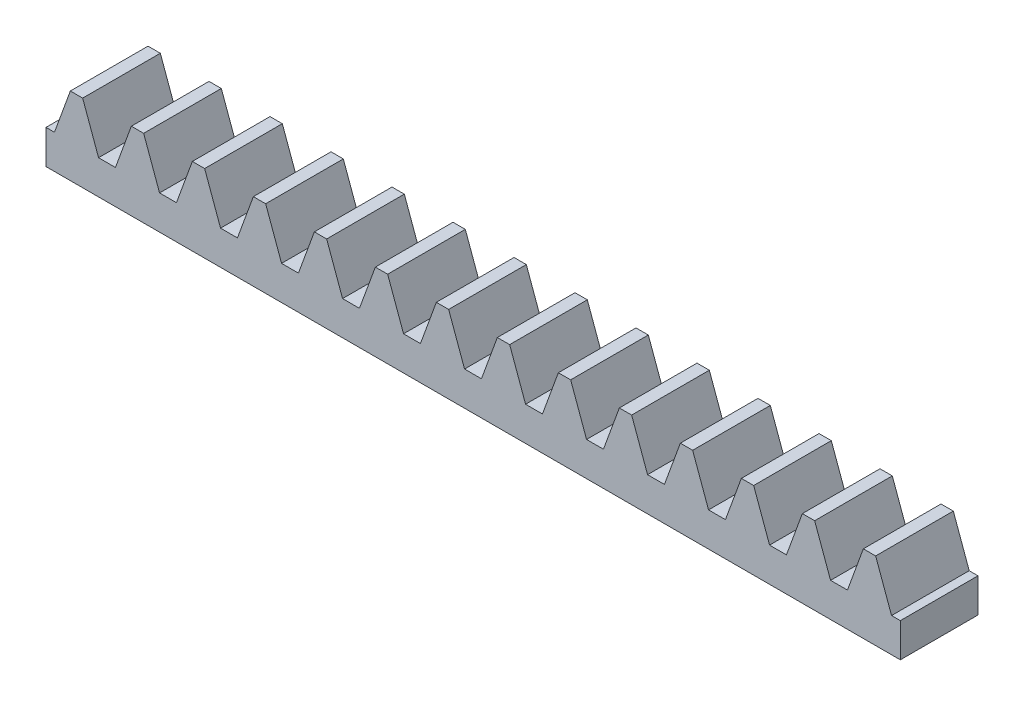
SolidWorks part; units mm, degrees
extrude "Blank" add sketch "BlankSke" against normal blind 10
sketch "BlankSke" plane through (0, 0, 0) normal (0, 0, 1) x (1, 0, 0)
  line L1 (0, 0) -> (110, 0)
  line L2 (0, 0) -> (0, 10)
  line L3 (0, 10) -> (110, 10)
  line L4 (110, 0) -> (110, 10)
  dimension "Length" = 110
  dimension "Blank_height" = 10
ref_plane "Plane1" through (0, 0, 0) normal (0, 0, 1) x (1, 0, 0)
ref_plane "Plane2" through (0, 0, 0) normal (0, 1, 0) x (1, 0, 0)
ref_plane "Plane3" through (0, 0, 0) normal (1, 0, 0) x (0, 0, -1)
sketch "HoldingSke" plane through (0, 0, 0) normal (0, 1, 0) x (1, 0, 0)
  line L0 (0, 0) -> (0.0557, 0.3961)
  line L1 (-15, 0) -> (100, 0) construction
  line L2 (0, 0) -> (-2.1039, 2.3779)
  line L3 (0, 0) -> (-11.863, 4.5341)
  line L4 (0, 0) -> (8.3015, 2.3804)
  line L5 (0, 0) -> (-23.7986, -8.8762)
  line L6 (0, 0) -> (-10.5278, -7.1032)
  line L9 (-71.009, 38.7566) -> (32.3572, 76.3788)
  line L10 (-76.2, 4.8779) -> (-68.7, 4.8779)
  line L11 (0, 0) -> (-10, 0)
  line L12 (-76.2, 101.6) -> (-76.113, 101.6)
  line L13 (24.9733, 27.94) -> (52.9518, 28.4284)
  line L14 (24.9733, 27.94) -> (24.9743, 27.94)
  line L15 (24.9733, 27.94) -> (100.4006, 29.5858)
  circle A0 centre (0, 0) radius 19.05
  circle A1 centre (0, 0) radius 3.75
  circle A2 centre (0, 0) radius 12.7
  dimension "MPH" = 7.5
  dimension "Diameter" = 38.1
  dimension "Num_teeth" = 16
  dimension "Pitch" = 0.4
  dimension "Show_teeth" = 998
  dimension "Thickness" = 12.7
  dimension "Ap" = 20
  dimension "Pitch_height" = 7.5
  dimension "Width" = 10
  dimension "Backlash" = 0.087
  dimension "Addendum_fac" = 1
  dimension "Dedendum_fac" = 1.25
  dimension "Clearance_fac" = 0.25
  dimension "Dedendum_add" = 0.001
  dimension "Length" = 110
  dimension "Module" = 2.5
sketch "TooCutSkeIll" plane through (0, 0, 0) normal (0, 0, 1) x (1, 0, 0)
  line L0 (-3.1105, 9.9342) -> (-1.237, 4.7869)
  line L1 (-0.6488, 4.375) -> (0.6488, 4.375)
  line L2 (1.237, 4.7869) -> (3.1105, 9.9342)
  line L3 (110, 10) -> (0, 10) construction
  line L4 (0, 0) -> (0, 64.897) construction
  line L5 (-13.208, 7.5) -> (12.954, 7.5) construction
  line L6 (0, 0) -> (110, 0) construction
  line L7 (2.2245, 7.5) -> (2.2245, 48.7463) construction
  line L8 (-2.2245, 7.5) -> (-2.2245, 48.7463) construction
  line L9 (3.2044, 10) -> (3.2044, 10.0254)
  line L10 (-3.2044, 10) -> (-3.2044, 10.0254)
  line L11 (-3.2044, 10.0254) -> (3.2044, 10.0254)
  arc A0 (0.6488, 4.375) -> (1.237, 4.7869) centre (0.6488, 5.001) ccw
  arc A1 (-1.237, 4.7869) -> (-0.6488, 4.375) centre (-0.6488, 5.001) ccw
  arc A2 (3.2044, 10) -> (3.1105, 9.9342) centre (3.2044, 9.9) ccw
  arc A3 (-3.1105, 9.9342) -> (-3.2044, 10) centre (-3.2044, 9.9) ccw
  dimension "Pitch_height" = 7.5
  dimension "Addendum_plus" = 2.5254
  dimension "Pressure_angle" = 20
  dimension "Gap_width" = 4.449
  dimension "Dedendum" = 3.125
extrude "ToothCutIll" [suppressed] cut sketch "TooCutSkeIll" against normal through all
sketch "TooCutSkeSim" plane through (0, 0, 0) normal (0, 0, 1) x (1, 0, 0)
  line L0 (1.0871, 4.375) -> (-1.0871, 4.375)
  line L1 (3.1437, 10.0254) -> (1.0871, 4.375)
  line L2 (0, 17.4625) -> (0, 53.467) construction
  line L3 (3.1437, 10.0254) -> (-3.1437, 10.0254)
  line L6 (-3.1437, 10.0254) -> (-1.0871, 4.375)
  line L9 (-2.2245, 7.5) -> (2.2245, 7.5) construction
  line L10 (0, 0) -> (110, 0) construction
  line L11 (2.2245, 7.5) -> (2.2245, 53.467) construction
  line L12 (-2.2245, 7.5) -> (-2.2245, 53.467) construction
  dimension "Pitch_height" = 7.5
  dimension "Addendum_plus" = 2.5254
  dimension "Pressure_angle" = 20
  dimension "Gap_width" = 4.449
  dimension "Dedendum" = 3.125
extrude "ToothCutSim" cut sketch "TooCutSkeSim" against normal through all
pattern_linear "TeethCuts" count 15 spacing 7.854 along (1, 0, 0) of "ToothCutIll", "ToothCutSim"
equation "' \"Module@HoldingSke\" = 6.35"
equation "' \"Num_teeth@HoldingSke\" = 12"
equation "' \"Ap@HoldingSke\" =  20"
equation "' \"Ap@HoldingSke\" = 20"
equation "' \"Width@HoldingSke\" = 0.25 * 25.4"
equation "' \"Show_teeth@HoldingSke\" = 500"
equation "' \"Backlash@HoldingSke\" = 0.009 * 25.4"
equation "' \"Addendum_fac@HoldingSke\" = 1.0"
equation "' \"Dedendum_fac@HoldingSke\" = 1.25"
equation "' \"Dedendum_add@HoldingSke\" = 0.00005 * 25.4"
equation "' \"Clearance_fac@HoldingSke\" = 0.25"
equation "' \"Pitch_height@HoldingSke\" = 1 * 25.4"
equation "' \"Length@HoldingSke\" = 4.71 * 25.4"
equation "\"Pitch@HoldingSke\" = 1 / \"Module@HoldingSke\""
equation "\"MPH@HoldingSke\" = \"Dedendum_fac@HoldingSke\" / \"Pitch@HoldingSke\" + 2 * \"Dedendum_add@HoldingSke\" + 0.002 * 25.4"
equation "\"MPH@HoldingSke\" = ((sgn( \"MPH@HoldingSke\" - \"Pitch_height@HoldingSke\")+1)*( \"MPH@HoldingSke\" - \"Pitch_height@HoldingSke\"))/2 + \"Pitch_height@HoldingSke\""
equation "\"Blank_height@BlankSke\" = \"Pitch_height@HoldingSke\" + \"Addendum_fac@HoldingSke\"  / \"Pitch@HoldingSke\" "
equation "\"Length@BlankSke\" =  \"Length@HoldingSke\""
equation "\"Face_width@Blank\" = \"Width@HoldingSke\""
equation "\"Pressure_angle@TooCutSkeIll\" = \"Ap@HoldingSke\""
equation "\"Addendum_plus@TooCutSkeIll\" =  \"Addendum_fac@HoldingSke\"  / \"Pitch@HoldingSke\" + 0.001 *25.4"
equation "\"Dedendum@TooCutSkeIll\" = \"Dedendum_fac@HoldingSke\"  / \"Pitch@HoldingSke\""
equation "\"Pitch_height@TooCutSkeIll\" =  \"MPH@HoldingSke\""
equation "\"Gap_width@TooCutSkeIll\" = 3.14159265 / 2 / \"Pitch@HoldingSke\" + 6 * \"Backlash@HoldingSke\""
equation "\"Pressure_angle@TooCutSkeSim\" = \"Ap@HoldingSke\""
equation "\"Addendum_plus@TooCutSkeSim\" =  \"Addendum_fac@HoldingSke\"  / \"Pitch@HoldingSke\" + 0.001 * 25.4"
equation "\"Dedendum@TooCutSkeSim\" = \"Dedendum_fac@HoldingSke\"  / \"Pitch@HoldingSke\""
equation "\"Pitch_height@TooCutSkeSim\" =  \"MPH@HoldingSke\""
equation "\"Gap_width@TooCutSkeSim\" = 3.14159265 / 2 / \"Pitch@HoldingSke\" + 6 * \"Backlash@HoldingSke\""
equation "\"Root_fillet@TooCutSkeIll\" = \"Clearance_fac@HoldingSke\" / \"Pitch@HoldingSke\" + \"Dedendum_add@HoldingSke\""
equation "\"Break_rad@TooCutSkeIll\" = 0.02 / \"Pitch@HoldingSke\" * 2"
equation "\"Linear_pitch@TeethCuts\" = 3.14159265 / \"Pitch@HoldingSke\""
equation "\"Num_teeth@HoldingSke\" = int( ( \"Length@HoldingSke\" + 0 ) / (3.14159265 / \"Pitch@HoldingSke\")) + 0.9999  + 1"
equation " \"Num_teeth@TeethCuts\" = int( \"Show_teeth@HoldingSke\" ) + 1"
equation " \"Num_teeth@TeethCuts\" = ((sgn( \"Num_teeth@TeethCuts\" - \"Num_teeth@HoldingSke\" )-1)*( \"Num_teeth@TeethCuts\" - \"Num_teeth@HoldingSke\" ))/-2+ \"Num_teeth@HoldingSke\""
equation " \"Num_teeth@TeethCuts\" = ((sgn( \"Num_teeth@TeethCuts\" - 2.0)+1)*( \"Num_teeth@TeethCuts\" - 2.0))/2 +2.0"
